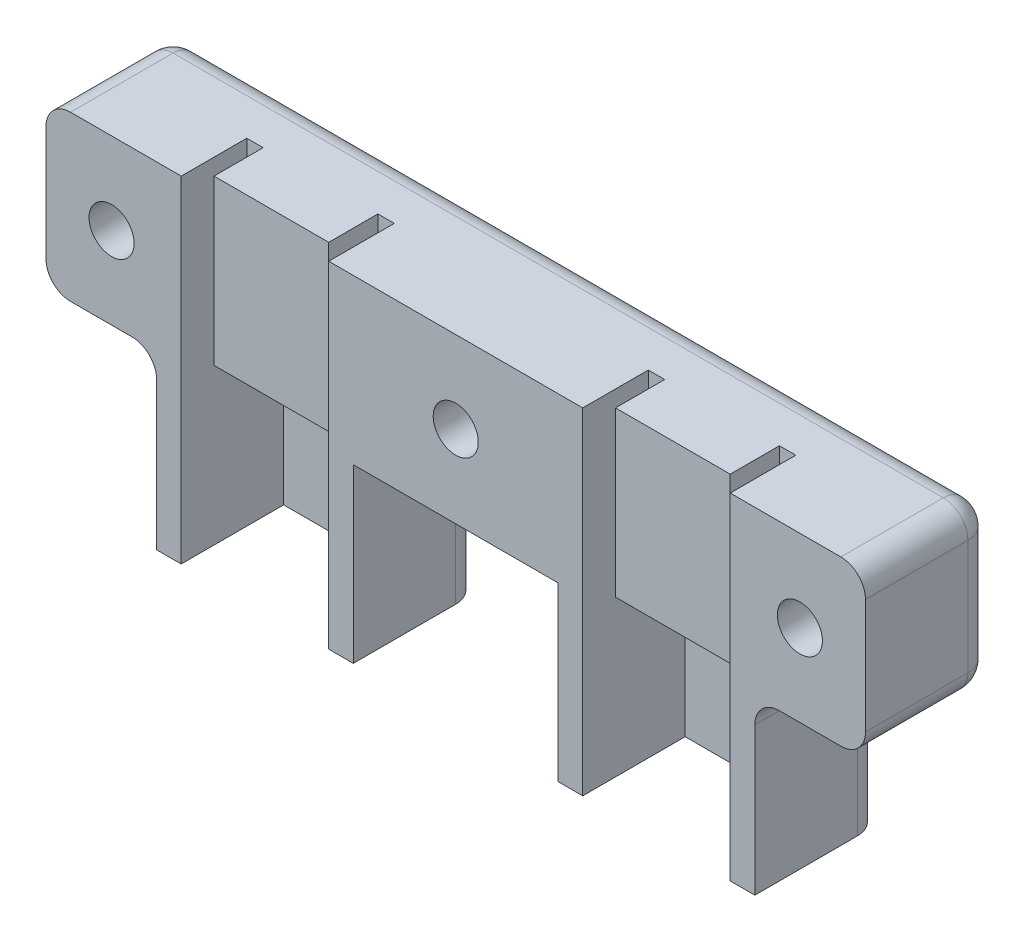
SolidWorks part; units mm, degrees
ref_plane "Front Plane" through (0, 0, 0) normal (0, 0, 1) x (1, 0, 0)
ref_plane "Top Plane" through (0, 0, 0) normal (0, 1, 0) x (1, 0, 0)
ref_plane "Right Plane" through (0, 0, 0) normal (1, 0, 0) x (0, 0, -1)
sketch "Sketch1" plane through (0, 0, 0) normal (0, 1, 0) x (1, 0, 0)
  line L0 (-32.5165, -1.8398) -> (-32.5165, 13.6602)
  line L1 (-32.5165, 13.6602) -> (67.4835, 13.6602)
  line L2 (17.4835, 19.0774) -> (17.4835, -21.7565) construction
  line L3 (-0.0165, 0.1602) -> (-14.0165, 0.1602)
  line L4 (-14.0165, 0.1602) -> (-14.0165, 6.1602)
  line L5 (-14.0165, 6.1602) -> (-16.0165, 6.1602)
  line L6 (-16.0165, 6.1602) -> (-16.0165, 1.6364)
  line L7 (-32.5165, -1.8398) -> (-16.0165, -1.8398)
  line L8 (-16.0165, -1.8398) -> (-16.0165, 1.6364)
  line L9 (-7.0165, 12.4346) -> (-7.0165, -12.2705) construction
  line L10 (1.9835, -1.8398) -> (1.9835, 1.6364)
  line L11 (1.9835, 6.1602) -> (1.9835, 1.6364)
  line L12 (-0.0165, 6.1602) -> (1.9835, 6.1602)
  line L13 (-0.0165, 0.1602) -> (-0.0165, 6.1602)
  line L15 (34.9835, 0.1602) -> (34.9835, 6.1602)
  line L16 (34.9835, 6.1602) -> (32.9835, 6.1602)
  line L17 (32.9835, 6.1602) -> (32.9835, 1.6364)
  line L18 (32.9835, -1.8398) -> (32.9835, 1.6364)
  line L19 (50.9835, -1.8398) -> (50.9835, 1.6364)
  line L20 (67.4835, -1.8398) -> (50.9835, -1.8398)
  line L21 (50.9835, 6.1602) -> (50.9835, 1.6364)
  line L22 (48.9835, 6.1602) -> (50.9835, 6.1602)
  line L23 (48.9835, 0.1602) -> (48.9835, 6.1602)
  line L24 (34.9835, 0.1602) -> (48.9835, 0.1602)
  line L25 (67.4835, -1.8398) -> (67.4835, 13.6602)
  line L26 (1.9835, -1.8398) -> (32.9835, -1.8398)
  point P15 (41.9835, 0.1602)
  point P18 (-7.0165, 0.1602)
  point P32 (17.4835, 13.6602)
  dimension "D1" = 7
  dimension "D2" = 8
  dimension "D3" = 2
  dimension "D4" = 6
  dimension "D5" = 15.5
  dimension "D6" = 16.5
extrude "Boss-Extrude1" add sketch "Sketch1" along normal blind 20
sketch "Sketch2" plane through (0, 0, 0) normal (0, -1, 0) x (1, 0, 0)
  line L0 (-17.5165, 1.8398) -> (-17.5165, -12.1602)
  line L1 (-32.5165, 1.8398) -> (-16.0165, 1.8398) construction
  line L2 (-17.5165, -12.1602) -> (3.4835, -12.1602)
  line L3 (3.4835, -12.1602) -> (3.4835, 1.8398)
  line L4 (-16.0165, 1.8398) -> (-16.0165, -6.1602) construction
  line L5 (1.9835, -6.1602) -> (1.9835, 1.8398) construction
  line L6 (17.4835, 8.9785) -> (17.4835, -37.4649) construction
  line L7 (-32.5165, -13.6602) -> (-32.5165, 1.8398) construction
  line L8 (52.4835, 1.8398) -> (52.4835, -12.1602)
  line L9 (52.4835, -12.1602) -> (31.4835, -12.1602)
  line L10 (31.4835, -12.1602) -> (31.4835, 1.8398)
  dimension "D1" = 1.5
  dimension "D2" = 1.5
  dimension "D3" = 14
  dimension "D4" = 50
extrude "Extrude-Thin3" add sketch "Sketch2" along normal blind 21 thin thin type mid plane wall 3
sketch "Sketch3" plane through (0, 0, -13.6602) normal (0, 0, -1) x (-1, 0, 0)
  line L3 (-17.4835, 44.3817) -> (-17.4835, -29.4557) construction
  circle A0 centre (24.5165, 10) radius 2.75
  circle A1 centre (-59.4835, 10) radius 2.75
  circle A2 centre (-17.4835, 10) radius 2.75
  dimension "D1" = 5.5
extrude "Cut-Extrude1" cut sketch "Sketch3" against normal through all
fillet "Fillet2" radius 3 16 edges at (29.9835, -10.5, -13.6602) (53.9835, -10.5, -13.6602) (67.4835, 0, -5.9102) (67.4835, 10, -13.6602) (67.4835, 20, -5.9102) (17.4835, 20, -13.6602) (-32.5165, 20, -5.9102) (-32.5165, 0, -5.9102) (-32.5165, 10, -13.6602) (53.9835, 0, -5.9102)
